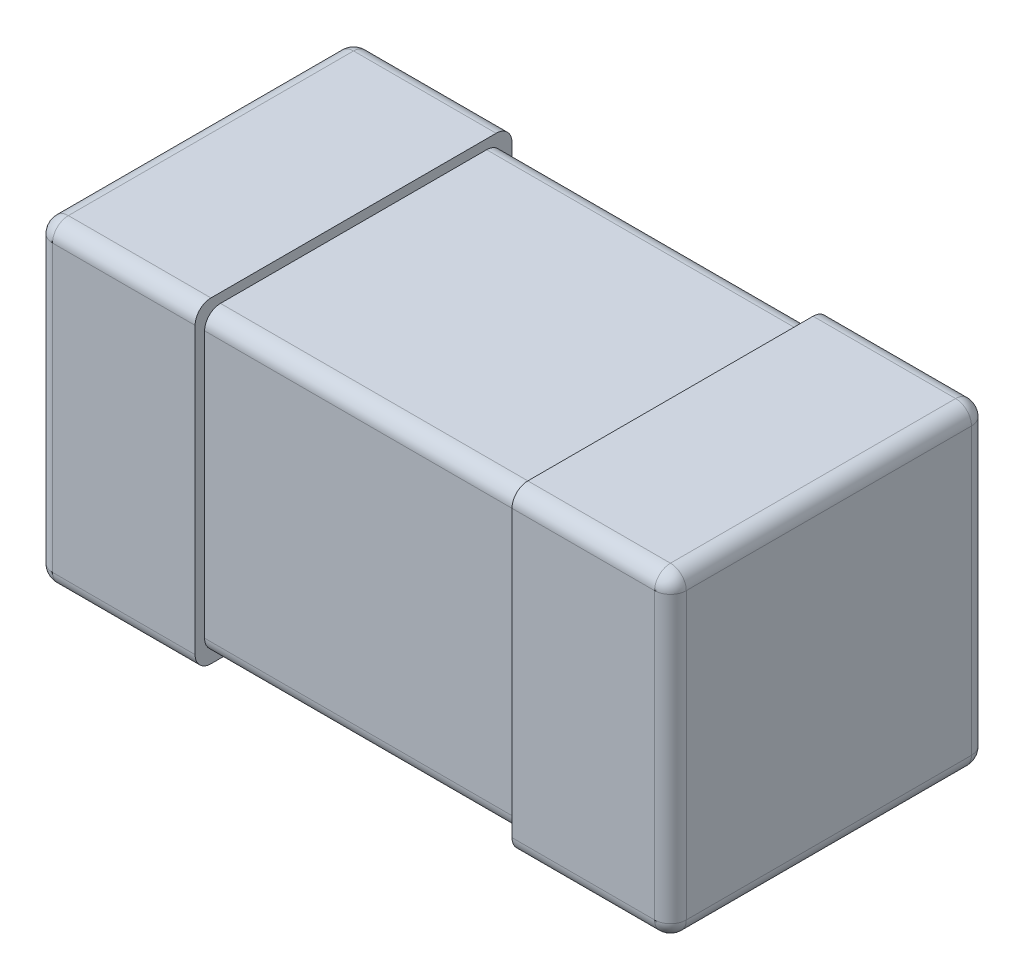
SolidWorks part; units mm, degrees
ref_plane "Спереди" through (0, 0, 0) normal (0, 0, 1) x (1, 0, 0)
ref_plane "Сверху" through (0, 0, 0) normal (0, 1, 0) x (1, 0, 0)
ref_plane "Справа" through (0, 0, 0) normal (1, 0, 0) x (0, 0, -1)
sketch "Эскиз3" plane through (0, 0, 0) normal (0, 0, 1) x (1, 0, 0)
  line L0 (0, 0.7005) -> (0, -0.7992) construction
  line L1 (0.5, 0.25) -> (0.5, -0.25)
  line L2 (0.5, 0.25) -> (0.25, 0.25)
  line L3 (0.25, 0.25) -> (0.25, -0.25)
  line L4 (0.5, -0.25) -> (0.25, -0.25)
  line L5 (-0.5, 0.25) -> (-0.25, 0.25)
  line L6 (-0.5, 0.25) -> (-0.5, -0.25)
  line L7 (-0.5, -0.25) -> (-0.25, -0.25)
  line L8 (-0.25, 0.25) -> (-0.25, -0.25)
  line L9 (-0.5, -0.25) -> (-0.25, 0.25) construction
  line L10 (-0.5, 0.25) -> (-0.25, -0.25) construction
  line L11 (0, 0) -> (-0.375, 0) construction
  point P11 (-0.375, 0)
  dimension "D1" = 0.25
  dimension "D2" = 0.5
  dimension "D3" = 1
extrude "Вытянуть3" add sketch "Эскиз3" along normal blind 0.5
sketch "Эскиз4" plane through (0, 0, 0) normal (0, 0, 1) x (1, 0, 0)
  line L1 (0.25, -0.235) -> (-0.25, -0.235)
  line L2 (0.25, -0.235) -> (0.25, 0.235)
  line L3 (0.25, 0.235) -> (-0.25, 0.235)
  line L4 (-0.25, -0.235) -> (-0.25, 0.235)
  line L5 (0.25, -0.235) -> (-0.25, 0.235) construction
  line L6 (0.25, 0.235) -> (-0.25, -0.235) construction
  line L7 (-0.25, -0.25) -> (-0.25, 0.25) construction
  point P0 (0, 0)
  dimension "D1" = 0.015
extrude "Бобышка-Вытянуть3" add sketch "Эскиз4" along normal offset from surface (0.47 mm away) 0.015 from offset 0.015 up to face at (-0.375, 0, 0.5)
fillet "Скругление2" radius 0.025 16 edges at (-0.5, 0.25, 0.25) (-0.5, 0, 0.5) (-0.5, -0.25, 0.25) (-0.5, 0, 0) (-0.375, 0.25, 0) (-0.375, -0.25, 0) (-0.375, 0.25, 0.5) (-0.375, -0.25, 0.5) (0.5, -0.25, 0.25) (0.5, 0, 0.5) (0.5, 0.25, 0.25) (0.5, 0, 0) (0.375, 0.25, 0) (0.375, 0.25, 0.5) (0.375, -0.25, 0.5) (0.375, -0.25, 0)
fillet "Скругление3" radius 0.025 4 edges at (0, -0.235, 0.015) (0, 0.235, 0.015) (0, 0.235, 0.485) (0, -0.235, 0.485)
